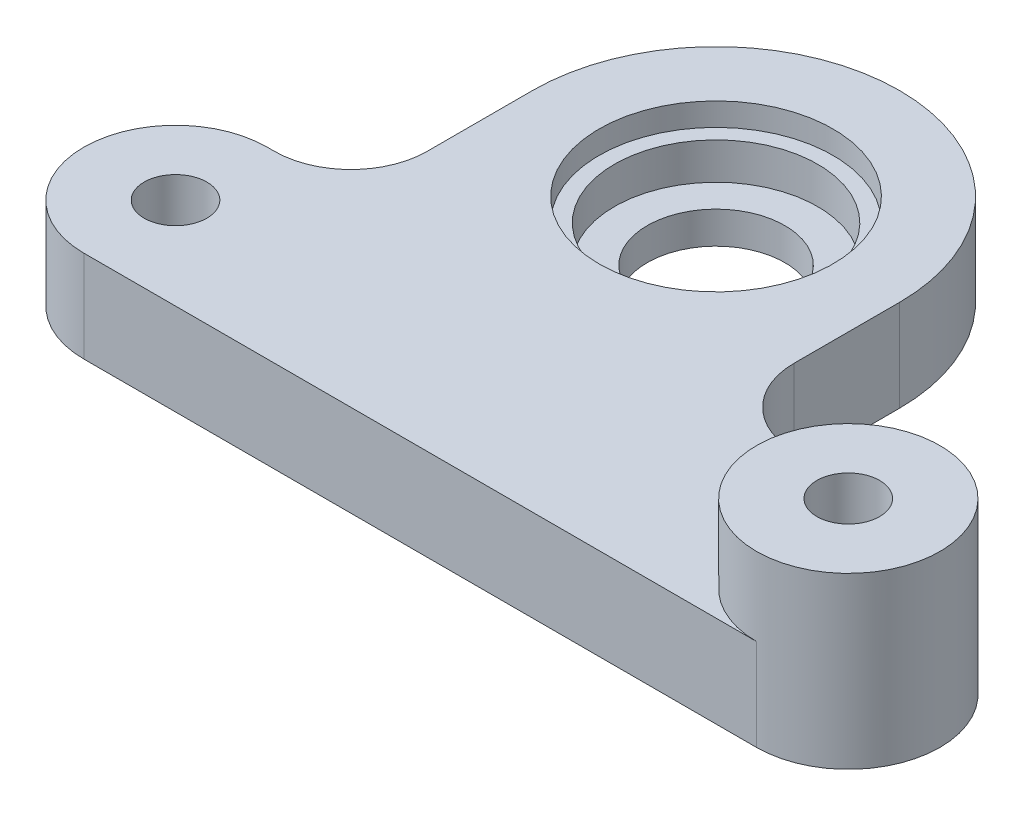
SolidWorks part; units mm, degrees
ref_plane "前视基准面" through (0, 0, 0) normal (0, 0, 1) x (1, 0, 0)
ref_plane "上视基准面" through (0, 0, 0) normal (0, 1, 0) x (1, 0, 0)
ref_plane "右视基准面" through (0, 0, 0) normal (1, 0, 0) x (0, 0, -1)
sketch "草图1" plane through (0, 0, 0) normal (0, 1, 0) x (1, 0, 0)
  line L0 (-14.1684, -10.0965) -> (29.8316, -10.0965)
  line L1 (-8.7025, 13.7904) -> (-8.7025, 6.9035)
  line L2 (-13.7025, 1.9035) -> (-14.1684, 1.9035)
  line L3 (15.2975, 13.7904) -> (15.2975, 6.9035)
  line L4 (20.2975, 1.9035) -> (29.8316, 1.9035)
  circle A0 centre (3.2975, 13.7904) radius 4.5
  circle A1 centre (-14.1684, -4.0965) radius 2.05
  circle A2 centre (29.8316, -4.0965) radius 2.05
  arc A3 (-14.1684, 1.9035) -> (-14.1684, -10.0965) centre (-14.1684, -4.0965) ccw
  arc A4 (15.2975, 13.7904) -> (-8.7025, 13.7904) centre (3.2975, 13.7904) ccw
  arc A5 (29.8316, -10.0965) -> (29.8316, 1.9035) centre (29.8316, -4.0965) ccw
  arc A6 (20.2975, 1.9035) -> (15.2975, 6.9035) centre (20.2975, 6.9035) cw
  arc A7 (-8.7025, 6.9035) -> (-13.7025, 1.9035) centre (-13.7025, 6.9035) cw
  point P22 (-8.7025, 1.9035)
  dimension "D4" = 4.1
  dimension "D5" = 9
  dimension "D6" = 12
  dimension "D7" = 24
  dimension "D8" = 5
  dimension "D1" = 44
  dimension "D2" = 32
  dimension "D3" = 25
extrude "凸台-拉伸1" add sketch "草图1" along normal blind 6
sketch "草图2" plane through (0, 0, 0) normal (0, -1, 0) x (1, 0, 0)
  circle A0 centre (-14.1684, 4.0965) radius 4
  circle A1 centre (29.8316, 4.0965) radius 4
  dimension "D1" = 8
extrude "切除-拉伸1" cut sketch "草图2" against normal blind 2
sketch "草图3" plane through (0, 6, 0) normal (0, 1, 0) x (1, 0, 0)
  circle A0 centre (3.2975, 13.7904) radius 6.65
  dimension "D1" = 13.3
extrude "切除-拉伸2" cut sketch "草图3" against normal blind 3.9
sketch "草图4" plane through (0, 6, 0) normal (0, 1, 0) x (1, 0, 0)
  circle A0 centre (3.2975, 13.7904) radius 7.65
  dimension "D1" = 15.3
extrude "切除-拉伸3" cut sketch "草图4" against normal blind 1.5
sketch "草图5" plane through (0, 6, 0) normal (0, 1, 0) x (1, 0, 0)
  circle A0 centre (29.8316, -4.0965) radius 6
  circle A1 centre (29.8316, -4.0965) radius 2.05
extrude "凸台-拉伸2" add sketch "草图5" along normal blind 5.1
